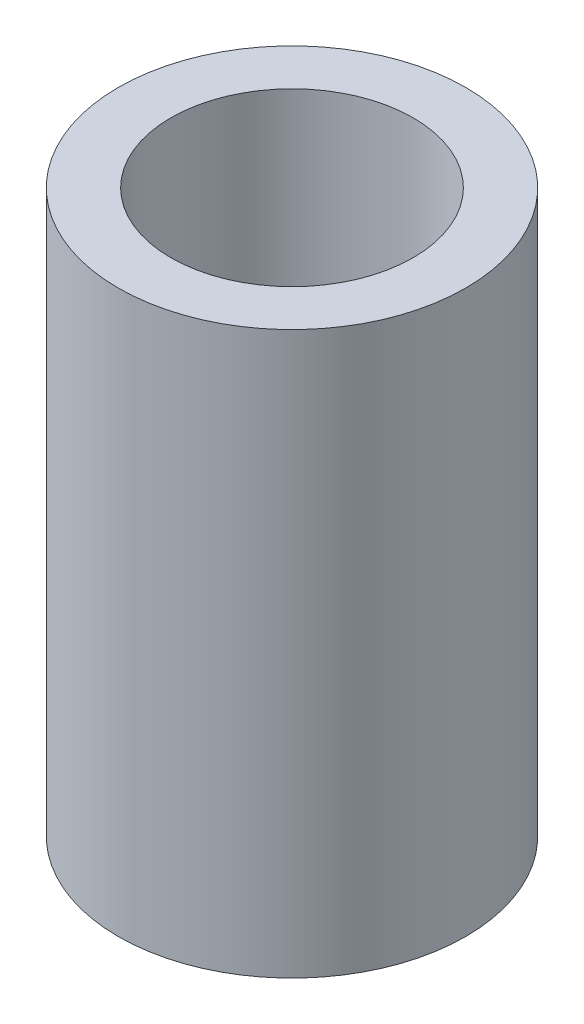
SolidWorks part; units mm, degrees
ref_plane "Front Plane" through (0, 0, 0) normal (0, 0, 1) x (1, 0, 0)
ref_plane "Top Plane" through (0, 0, 0) normal (0, 1, 0) x (1, 0, 0)
ref_plane "Right Plane" through (0, 0, 0) normal (1, 0, 0) x (0, 0, -1)
ref_plane "Plane1" through (0, 23.2214, 0) normal (0, -1, 0) x (-1, 0, 0)
ref_plane "Plane2" through (0, -20.2126, 0) normal (0, 1, 0) x (1, 0, 0)
sketch "Sketch1" plane through (0, 23.2214, 0) normal (0, -1, 0) x (1, 0, 0)
  circle A0 centre (-4.0978, 0.3551) radius 13.4366 construction
  circle A1 centre (-4.0978, 0.3551) radius 13.4366
  circle A2 centre (-4.0978, 0.3551) radius 9.3726 construction
  circle A3 centre (-4.0978, 0.3551) radius 9.3726
extrude "Boss-Extrude1" add sketch "Sketch1" along normal up to surface (43.434 mm away) up to plane "Plane2"
